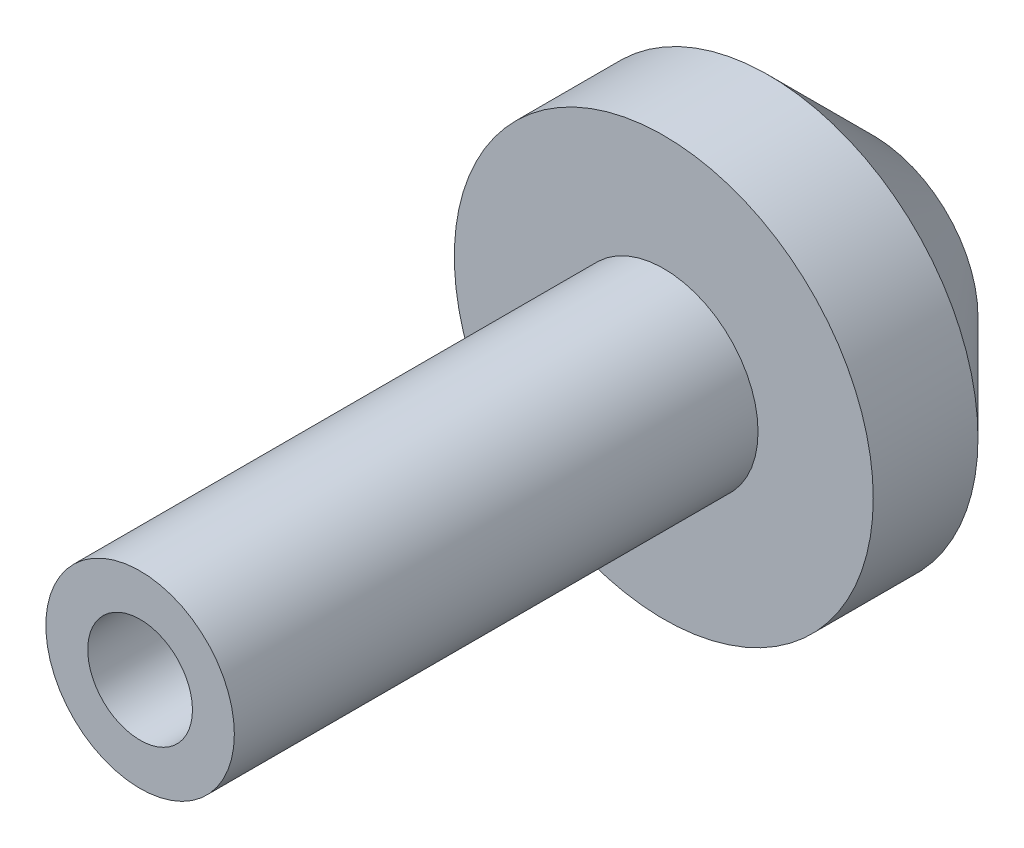
SolidWorks part; units mm, degrees
ref_plane "Front Plane" through (0, 0, 0) normal (0, 0, 1) x (1, 0, 0)
ref_plane "Top Plane" through (0, 0, 0) normal (0, 1, 0) x (1, 0, 0)
ref_plane "Right Plane" through (0, 0, 0) normal (1, 0, 0) x (0, 0, -1)
sketch "Sketch1" plane through (0, 0, 0) normal (0, 0, 1) x (1, 0, 0)
  circle A0 centre (0, 0) radius 5
  dimension "D1" = 10
extrude "Boss-Extrude1" add sketch "Sketch1" along normal blind 5
sketch "Sketch2" plane through (0, 0, 5) normal (0, 0, 1) x (1, 0, 0)
  circle A0 centre (0, 0) radius 2.25
  dimension "D1" = 4.5
extrude "Boss-Extrude2" add sketch "Sketch2" along normal blind 12.5
sketch "Sketch3" plane through (0, 0, 17.5) normal (0, 0, 1) x (1, 0, 0)
  circle A0 centre (0, 0) radius 1.25
  dimension "D1" = 2.5
extrude "Cut-Extrude1" cut sketch "Sketch3" against normal blind 10
chamfer "Chamfer1" distance 2.5 angle 45 1 edges at (5, 0, 0)
